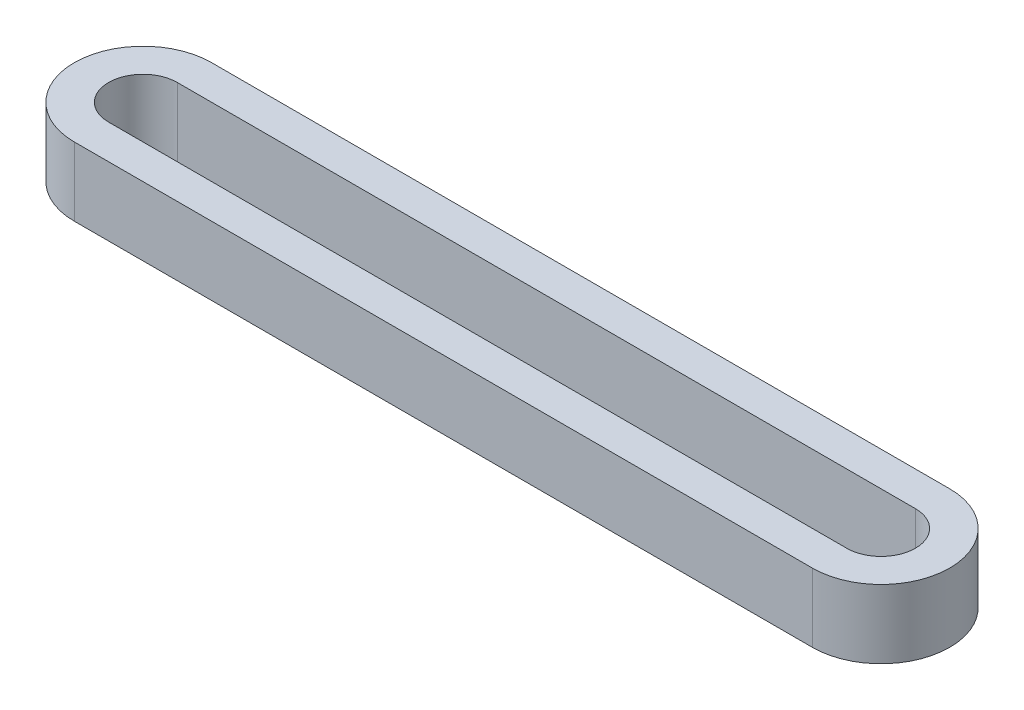
SolidWorks part; units mm, degrees
ref_plane "前视基准面" through (0, 0, 0) normal (0, 0, 1) x (1, 0, 0)
ref_plane "上视基准面" through (0, 0, 0) normal (0, 1, 0) x (1, 0, 0)
ref_plane "右视基准面" through (0, 0, 0) normal (1, 0, 0) x (0, 0, -1)
sketch "草图1" plane through (0, 0, 0) normal (0, 1, 0) x (1, 0, 0)
  line L0 (-10.75, 0) -> (10.75, 0) construction
  line L1 (-10.75, 1) -> (10.75, 1)
  line L2 (-10.75, -1) -> (10.75, -1)
  line L3 (-10.75, 0) -> (10.75, 0) construction
  line L4 (-10.75, 2) -> (10.75, 2)
  line L5 (-10.75, -2) -> (10.75, -2)
  arc A0 (-10.75, 1) -> (-10.75, -1) centre (-10.75, 0) ccw
  arc A1 (10.75, -1) -> (10.75, 1) centre (10.75, 0) ccw
  arc A2 (-10.75, 2) -> (-10.75, -2) centre (-10.75, 0) ccw
  arc A3 (10.75, -2) -> (10.75, 2) centre (10.75, 0) ccw
  point P2 (0, 0)
  point P10 (0, 0)
  dimension "D2" = 1
  dimension "D3" = 1
  dimension "D1" = 21.5
extrude "凸台-拉伸1" add sketch "草图1" along normal blind 2
